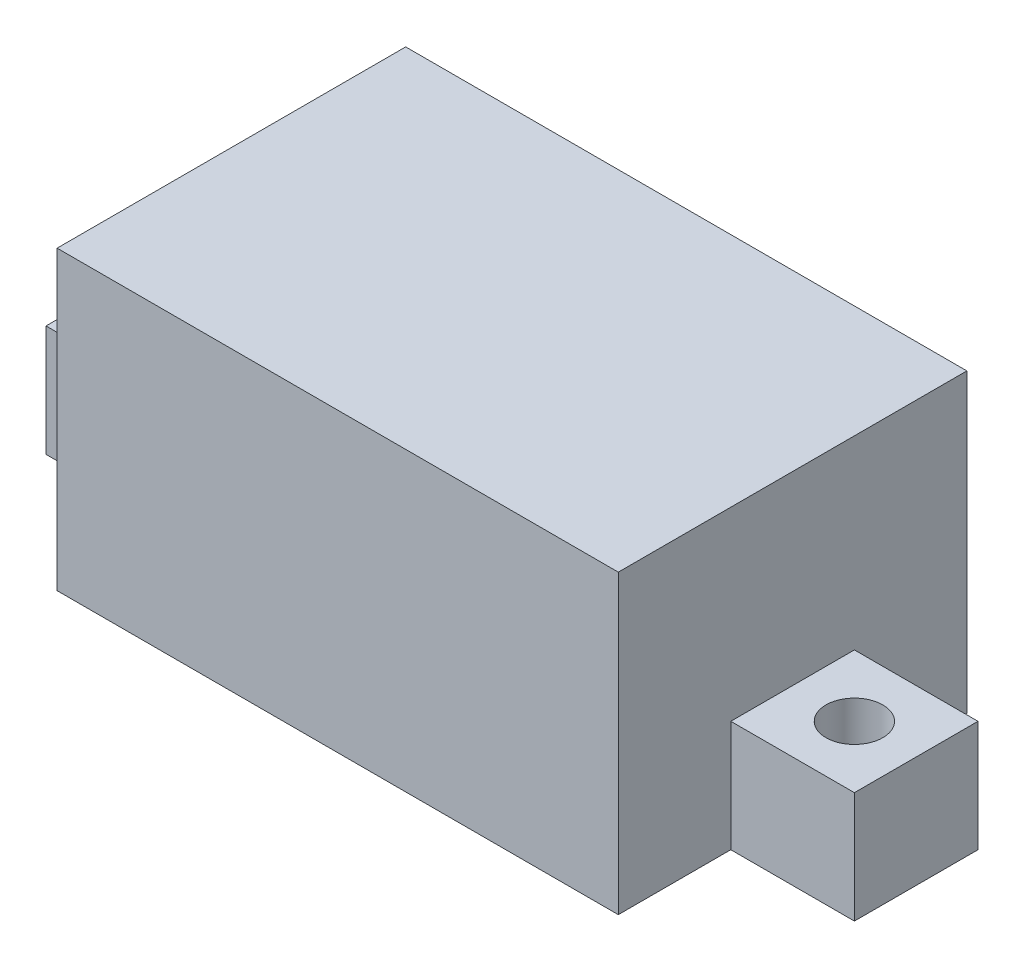
SolidWorks part; units mm, degrees
ref_plane "Front" through (0, 0, 0) normal (0, 0, 1) x (1, 0, 0)
ref_plane "Top" through (0, 0, 0) normal (0, 1, 0) x (1, 0, 0)
ref_plane "Right" through (0, 0, 0) normal (1, 0, 0) x (0, 0, -1)
sketch "ｽｹｯﾁ1" plane through (0, 0, 0) normal (0, 1, 0) x (1, 0, 0)
  line L0 (11.35, 14.1) -> (11.35, 0) construction
  line L1 (0, 0) -> (22.7, 0)
  line L2 (0, 0) -> (0, 14.1)
  line L3 (0, 14.1) -> (22.7, 14.1)
  line L4 (22.7, 0) -> (22.7, 14.1)
  line L6 (0, 10.8825) -> (0, 3.2175)
  line L10 (0, 7.05) -> (22.7, 7.05) construction
  dimension "D1" = 22.7
  dimension "D2" = 14.1
extrude "ﾎﾞｽ - 押し出し1" add sketch "ｽｹｯﾁ1" along normal blind 12 contours L1 L4 L3 L2
sketch "ｽｹｯﾁ2" plane through (0, 0, 0) normal (0, -1, 0) x (1, 0, 0)
  line L0 (0, -7.05) -> (22.7, -7.05) construction
  line L1 (0, 0) -> (0, -14.1) construction
  line L2 (22.7, 0) -> (22.7, -14.1) construction
  line L4 (-5, -7.05) -> (0, -7.05) construction
  line L5 (0, -4.55) -> (-5, -4.55)
  line L6 (0, -4.55) -> (0, -9.55)
  line L7 (0, -9.55) -> (-5, -9.55)
  line L8 (-5, -4.55) -> (-5, -9.55)
  line L9 (11.35, 0) -> (11.35, -14.1) construction
  line L10 (0, 0) -> (22.7, 0) construction
  line L11 (0, -14.1) -> (22.7, -14.1) construction
  line L12 (27.7, -7.05) -> (22.7, -7.05) construction
  line L13 (27.7, -4.55) -> (27.7, -9.55)
  line L14 (22.7, -9.55) -> (27.7, -9.55)
  line L15 (22.7, -4.55) -> (22.7, -9.55)
  line L16 (22.7, -4.55) -> (27.7, -4.55)
  circle A0 centre (-2.5, -7.05) radius 1.15
  circle A1 centre (25.2, -7.05) radius 1.15
  dimension "D3" = 2.3
  dimension "D1" = 5
  dimension "D2" = 5
extrude "ﾎﾞｽ - 押し出し2" add sketch "ｽｹｯﾁ2" against normal blind 4.5
ref_plane "平面1" through (0, 0, -7.05) normal (0, 0, 1) x (1, 0, 0)
ref_plane "平面2" through (11.35, 0, 0) normal (1, 0, 0) x (0, 0, -1)
